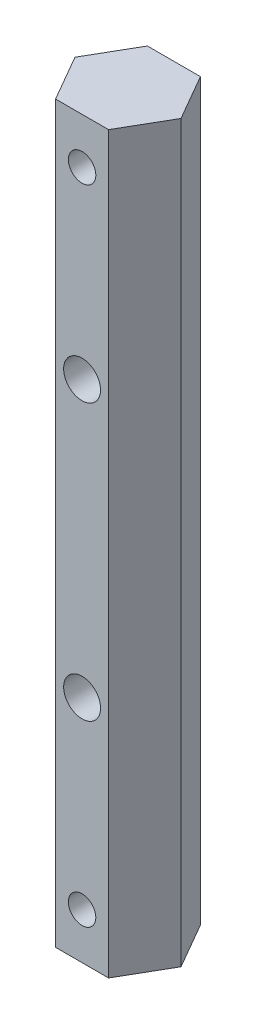
SolidWorks part; units mm, degrees
material "AISI 304"
ref_plane "Front Plane" through (0, 0, 0) normal (0, 0, 1) x (1, 0, 0)
ref_plane "Top Plane" through (0, 0, 0) normal (0, 1, 0) x (1, 0, 0)
ref_plane "Right Plane" through (0, 0, 0) normal (1, 0, 0) x (0, 0, -1)
sketch "Sketch1" plane through (0, 0, 0) normal (0, 1, 0) x (1, 0, 0)
  line L1 (7.3323, 0) -> (3.6662, 6.35)
  line L2 (3.6662, 6.35) -> (-3.6662, 6.35)
  line L3 (-3.6662, 6.35) -> (-7.3323, 0)
  line L4 (-7.3323, 0) -> (-3.6662, -6.35)
  line L5 (-3.6662, -6.35) -> (3.6662, -6.35)
  line L6 (3.6662, -6.35) -> (7.3323, 0)
  circle A0 centre (0, 0) radius 6.35 construction
  dimension "D1" = 12.7
extrude "Boss-Extrude1" add sketch "Sketch1" along normal blind 101.6
hole_wizard "Tap Drill for #10-24 Tap1" positions "Sketch2" profile "Sketch3" hole size "#10-24" standard "ANSI Inch" end condition through all
sketch "Sketch2" plane through (0, 0, 6.35) normal (0, 0, 1) x (1, 0, 0)
  line L0 (-3.6662, 50.8) -> (3.6662, 50.8) construction
  line L1 (-3.6662, 101.6) -> (-3.6662, 0) construction
  line L2 (3.6662, 101.6) -> (3.6662, 0) construction
  point P0 (0, 95.25)
  point P2 (0, 6.35)
  point P13 (0, 50.8)
  dimension "D1" = 88.9
sketch "Sketch3" plane through (0, 95.25, 6.35) normal (1, 0, 0) x (0, -1, 0)
  line L0 (0, 0) -> (0, 12.7)
  line L1 (0, 12.7) -> (1.8986, 12.7)
  line L2 (1.8986, 12.7) -> (1.8986, 0)
  line L5 (1.8986, 0) -> (0, 0)
  line L11 (0, -6.35) -> (0, 107.95) construction
  dimension "Thru Hole Dia." = 3.7973
  dimension "Thru Hole Depth" = 12.7
hole_wizard "Tap Drill for #10-24 Tap2" positions "Sketch4" profile "Sketch5" hole size "#10-24" standard "ANSI Inch"
sketch "Sketch4" plane through (0, 0, -6.35) normal (0, 0, 1) x (1, 0, 0)
  line L0 (-3.6662, 82.55) -> (3.6662, 82.55) construction
  line L1 (-3.6662, 165.1) -> (-3.6662, 0) construction
  line L2 (3.6662, 165.1) -> (3.6662, 0) construction
  point P0 (0, 156.6)
  point P2 (0, 143.9)
  point P4 (0, 8.5)
  point P6 (0, 21.2)
  dimension "D1" = 148.1
  dimension "D2" = 122.7
sketch "Sketch5" plane through (0, 156.6, 6.35) normal (1, 0, 0) x (0, -1, 0)
  line L0 (0, 0) -> (0, 12.7)
  line L1 (0, 12.7) -> (1.8986, 12.7)
  line L2 (1.8986, 12.7) -> (1.8986, 0)
  line L5 (1.8986, 0) -> (0, 0)
  line L11 (0, -6.35) -> (0, 107.95) construction
  dimension "Thru Hole Dia." = 3.7973
  dimension "Thru Hole Depth" = 12.7
sketch "Sketch6" plane through (0, 0, 6.35) normal (0, 0, 1) x (1, 0, 0)
  line L0 (-3.6662, 50.8) -> (3.6662, 50.8) construction
  line L1 (-3.6662, 101.6) -> (-3.6662, 0) construction
  line L2 (3.6662, 101.6) -> (3.6662, 0) construction
  circle A0 centre (0, 31.75) radius 2.5527
  circle A1 centre (0, 69.85) radius 2.5527
  dimension "D2" = 5.1054
  dimension "D1" = 38.1
extrude "Cut-Extrude1" cut sketch "Sketch6" against normal through all
equation "\"Length\"= 7.875"
